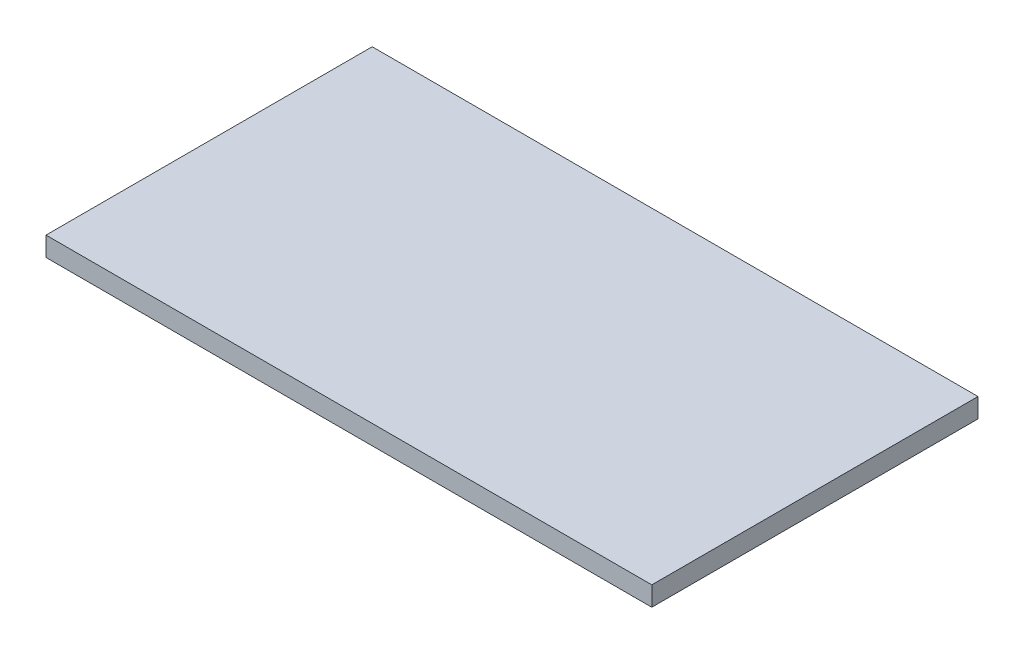
SolidWorks part; units mm, degrees
ref_plane "Front Plane" through (0, 0, 0) normal (0, 0, 1) x (1, 0, 0)
ref_plane "Top Plane" through (0, 0, 0) normal (0, 1, 0) x (1, 0, 0)
ref_plane "Right Plane" through (0, 0, 0) normal (1, 0, 0) x (0, 0, -1)
sketch "Sketch1" plane through (0, 0, 0) normal (0, 1, 0) x (1, 0, 0)
  line L1 (0, 0) -> (39.624, 0)
  line L2 (0, 0) -> (0, 21.336)
  line L3 (0, 21.336) -> (39.624, 21.336)
  line L4 (39.624, 0) -> (39.624, 21.336)
  point P9 (0, 0)
  dimension "D1" = 21.336
  dimension "D2" = 39.624
extrude "Boss-Extrude1" add sketch "Sketch1" against normal blind 1.27
sketch "Sketch3" plane through (39.624, 0, 0) normal (1, 0, 0) x (0, 0, -1)
  circle A0 centre (21.336, 0) radius 1.27
  point P2 (-0.0587, -0.1061)
  point P3 (1.5738, -0.2741)
  point P4 (1.7193, -0.1061)
  point P5 (1.778, 0)
